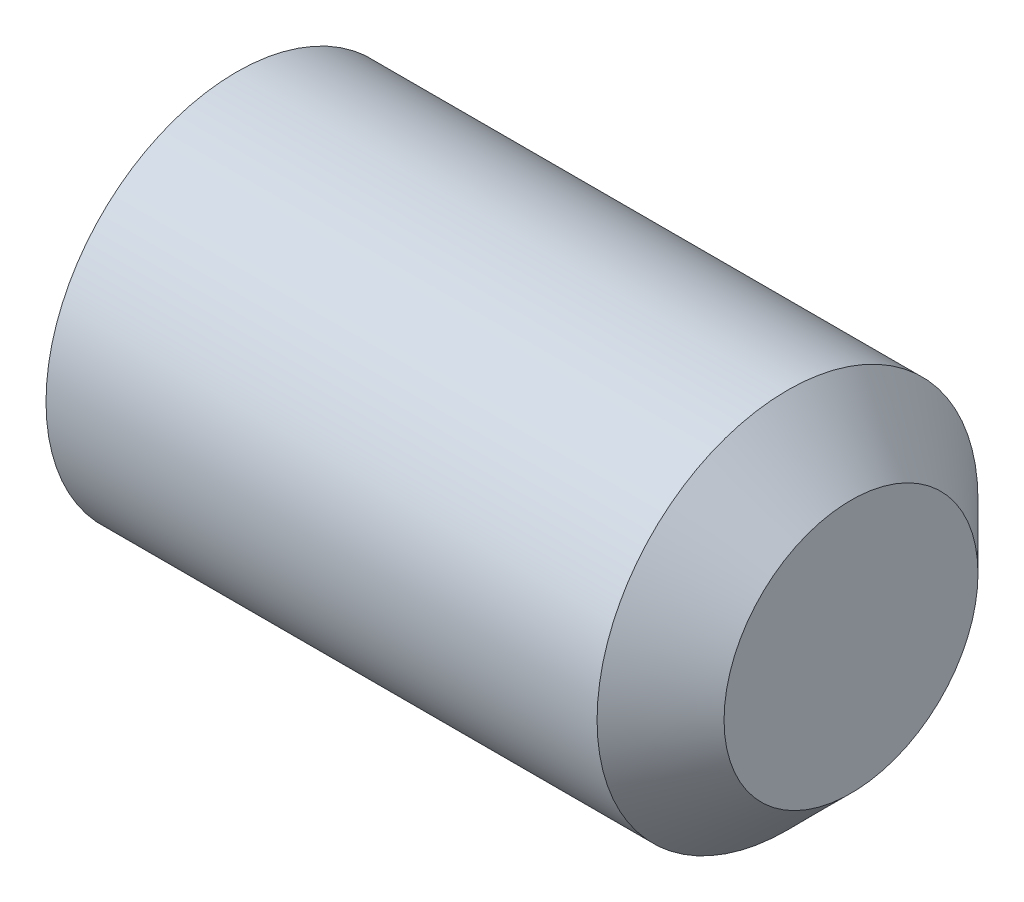
SolidWorks part; units mm, degrees
revolve "BaseBody" add sketch "BodySke" angle 360 about L5
sketch "BodySke" plane through (0, 0, 0) normal (0, 0, 1) x (1, 0, 0)
  line L0 (0, 0) -> (0, 2.4455)
  line L1 (0, 2.4455) -> (0.3201, 3)
  line L2 (0.3201, 3) -> (9, 3)
  line L3 (9, 3) -> (10, 2)
  line L4 (10, 0) -> (0, 0)
  line L5 (-12.7, 0) -> (88.9, 0) construction
  line L6 (10, 2) -> (10, 0)
  line L7 (10, 2) -> (10, 11.525) construction
  line L8 (0, -2.4455) -> (0.3201, -3) construction
  line L9 (1, 15.875) -> (1, -3.175) construction
  line L10 (9, -3) -> (10, -2) construction
  dimension "Diameter" = 6
  dimension "Drive_ch_ang" = 60
  dimension "Minor_dia" = 4.891
  dimension "Cup_nose_ang" = 45
  dimension "Cup_dia" = 4
  dimension "Length" = 10
  dimension "Advance" = 1
cosmetic thread "ThreadCosmetic" parameters "Thread_minor"=4.891
ref_plane "Plane1" through (0, 0, 0) normal (0, 0, 1) x (1, 0, 0)
ref_plane "Plane2" through (0, 0, 0) normal (0, 1, 0) x (1, 0, 0)
ref_plane "Plane3" through (0, 0, 0) normal (1, 0, 0) x (0, 0, -1)
sketch "Sketch2" plane through (0, 0, 0) normal (-1, 0, 0) x (0, 0, 1)
  line L0 (0.866, 1.5) -> (-0.866, 1.5)
  line L1 (-0.866, 1.5) -> (-1.7321, 0)
  line L2 (0.866, 1.5) -> (1.7321, 0)
  line L3 (0.866, -1.5) -> (1.7321, 0)
  line L4 (0.866, -1.5) -> (-0.866, -1.5)
  line L5 (-0.866, -1.5) -> (-1.7321, 0)
  dimension "Hex_size" = 3
  dimension "D2" = 1.5
  dimension "D3" = 1.5
extrude "Hex" cut sketch "Sketch2" against normal blind 3.5
sketch "ThdSchSke" plane through (0, 0, 0) normal (0, 0, 1) x (1, 0, 0)
  line L0 (0.3201, -2.4455) -> (-0.0681, -3)
  line L1 (0.3201, -2.4455) -> (0.7084, -3)
  line L2 (0.7084, -3) -> (0.7084, -3.75)
  line L3 (-3.175, 0) -> (5.1513, 0) construction
  line L5 (0.7084, -3.75) -> (-0.0681, -3.75)
  line L6 (-0.0681, -3.75) -> (-0.0681, -3)
  line L8 (0.3201, 3) -> (0.3201, -3) construction
  dimension "Thread_minor" = 4.891
  dimension "Diameter" = 6
revolve "ThreadSchematic" [suppressed] cut sketch "ThdSchSke" angle 360 about L3
pattern_linear "ThdSchPat" [suppressed]
equation "\"D2@Sketch2\" = \"Hex_size@Sketch2\" / 2"
equation "\"D3@Sketch2\" = \"Hex_size@Sketch2\" / 2"
equation "\"Thread_minor@ThreadCosmetic\" = \"Minor_dia@BodySke\""
equation "\"Thread_minor@ThdSchSke\" = \"Thread_minor@ThreadCosmetic\""
equation "\"Diameter@ThdSchSke\" = \"Diameter@BodySke\""
equation "\"Overcut@ThdSchSke\" = \"Diameter@BodySke\" * 1.25"
equation "\"Num_threads@ThdSchPat\" = int( (\"Length@BodySke\" - ( ( ( \"Diameter@BodySke\" - \"Minor_dia@BodySke\" ) * 0.5 ) / tan( \"Drive_ch_ang@BodySke\" * 0.017453292 ) ) - ( ( ( \"Diameter@BodySke\" - \"Cup_dia@BodySke\" ) * 0.5 ) * tan( \"Cup_nose_ang@BodySke\" * 0.017453292 ) ) ) / \"Advance@BodySke\" + 0.999 )  + 1"
equation "\"Advance@ThdSchPat\" = (\"Length@BodySke\" - ( ( ( \"Diameter@BodySke\" - \"Minor_dia@BodySke\" ) * 0.5 ) / tan( \"Drive_ch_ang@BodySke\" * 0.017453292 ) ) - ( ( ( \"Diameter@BodySke\" - \"Cup_dia@BodySke\" ) * 0.5 ) * tan( \"Cup_nose_ang@BodySke\" * 0.017453292 ) ) ) /  (\"Num_threads@ThdSchPat\" - 1) 'relax it"
equation "' \"Num_threads@ThdSchPat\" = \"Num_threads@ThdSchPat\" - sgn( \"Num_threads@ThdSchPat\" - 1) '---chamfered tips only---"
